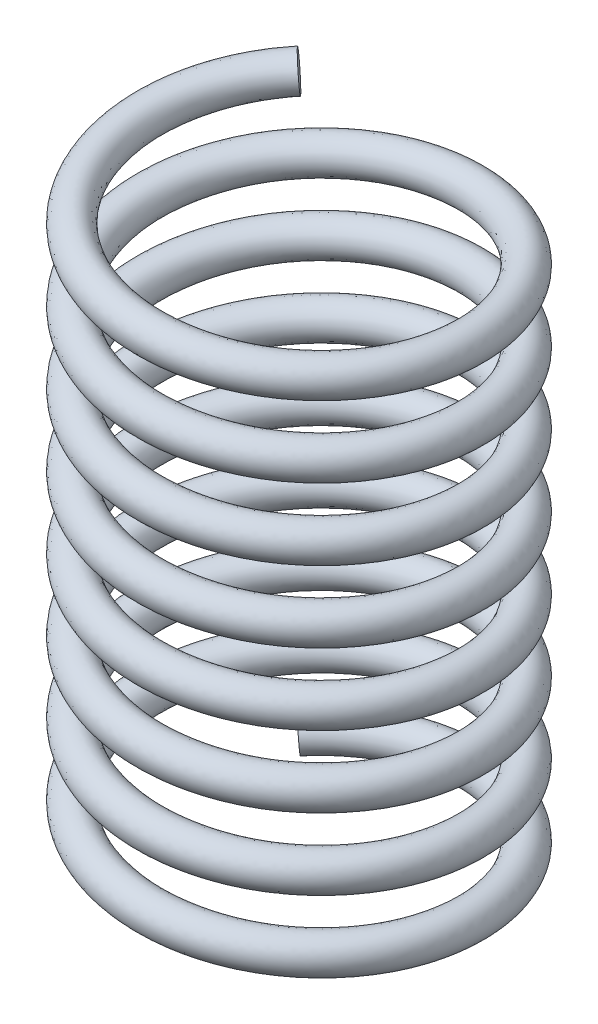
SolidWorks part; units mm, degrees
material "Plain Carbon Steel"
ref_plane "Front Plane" through (0, 0, 0) normal (0, 0, 1) x (1, 0, 0)
ref_plane "Top Plane" through (0, 0, 0) normal (0, 1, 0) x (1, 0, 0)
ref_plane "Right Plane" through (0, 0, 0) normal (1, 0, 0) x (0, 0, -1)
sketch "Sketch1" plane through (0, 0, 0) normal (0, 1, 0) x (1, 0, 0)
  circle A0 centre (0, 0) radius 4.5
  dimension "D1" = 9
curve "Helix/Spiral1" pitch 2 height 16 turns 8
ref_plane "Plane1" through (-3.182, 16, -3.182) normal (0.7053, 0.0706, -0.7053) x (-0.6992, -0.0944, -0.7087)
sketch "Sketch2" plane through (-3.182, 16, -3.182) normal (0.7053, 0.0706, -0.7053) x (-0.6992, -0.0944, -0.7087)
  circle A0 centre (0, 0) radius 0.5
  dimension "D1" = 1
sweep "Sweep1" add profiles "Sketch2" path "Helix/Spiral1"
equation "\"`1\"=1.31119"
